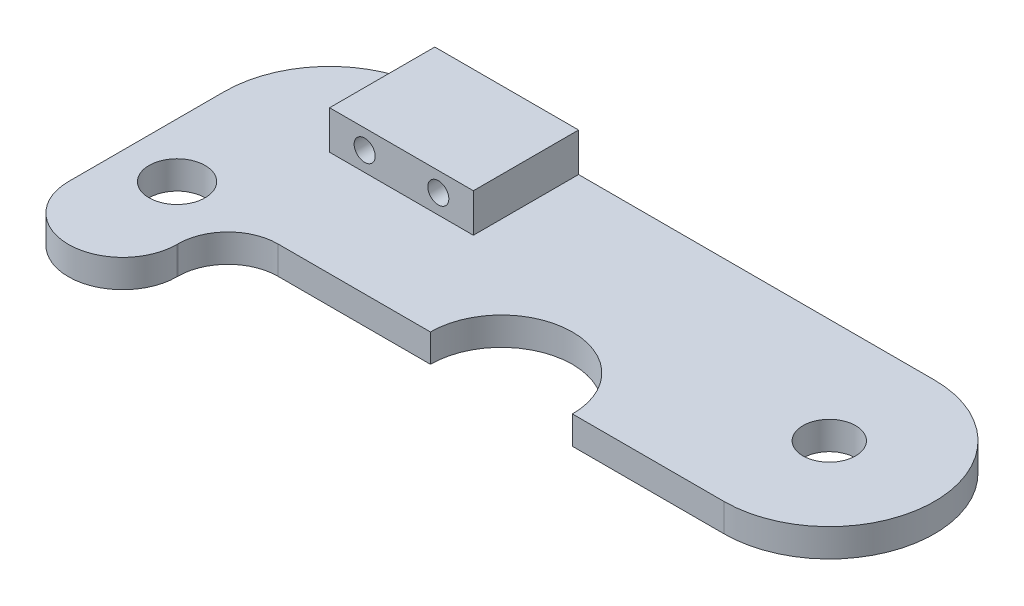
SolidWorks part; units mm, degrees
ref_plane "Front Plane" through (0, 0, 0) normal (0, 0, 1) x (1, 0, 0)
ref_plane "Top Plane" through (0, 0, 0) normal (0, 1, 0) x (1, 0, 0)
ref_plane "Right Plane" through (0, 0, 0) normal (1, 0, 0) x (0, 0, -1)
sketch "Sketch1" plane through (0, 0, 0) normal (0, 1, 0) x (1, 0, 0)
  line L0 (71.9495, -40.7752) -> (158.4495, -40.7752)
  line L1 (-126.5505, 79.2248) -> (158.4495, 79.2248)
  line L3 (-96.0505, -40.7752) -> (-9.0505, -40.7752)
  line L8 (-186.5505, -40.7752) -> (-186.5505, 19.2248)
  line L11 (-186.5505, -40.7752) -> (-186.5505, -69.7752)
  line L13 (-124.5505, -69.2752) -> (-124.5505, -69.7752)
  arc A0 (71.9495, -40.7752) -> (-9.0505, -40.7752) centre (31.4495, -40.7752) ccw
  circle A1 centre (158.4495, 19.2248) radius 15
  arc A2 (158.4495, -40.7752) -> (158.4495, 79.2248) centre (158.4495, 19.2248) ccw
  arc A3 (-126.5505, 79.2248) -> (-186.5505, 19.2248) centre (-126.5505, 19.2248) ccw
  arc A5 (-186.5505, -69.7752) -> (-124.5505, -69.7752) centre (-155.5505, -69.7752) ccw
  circle A6 centre (-155.5505, -38.7752) radius 16
  arc A7 (-96.0505, -40.7752) -> (-124.5505, -69.2752) centre (-96.0505, -69.2752) ccw
  point P14 (0, 0)
  dimension "D3" = 30
  dimension "D4" = 81
  dimension "D8" = 32
  dimension "D1" = 285
  dimension "D2" = 87
  dimension "D6" = 60
  dimension "D7" = 62
  dimension "D9" = 31
extrude "Boss-Extrude2" add sketch "Sketch1" along normal blind 16
scale "Scale1" scale about centroid uniform scaling yes scale factor 0.1
sketch "Sketch2" plane through (0, 8.8, 0) normal (0, 1, 0) x (1, 0, 0)
  line L1 (-12.8704, 21.7021) -> (-4.6704, 21.7021)
  line L2 (-12.8704, 21.7021) -> (-12.8704, 15.7021)
  line L3 (-12.8704, 15.7021) -> (-4.6704, 15.7021)
  line L4 (-4.6704, 21.7021) -> (-4.6704, 15.7021)
  dimension "D1" = 6
  dimension "D2" = 8.2
extrude "Boss-Extrude3" add sketch "Sketch2" along normal blind 2.2
sketch "Sketch3" plane through (0, 0, -21.7021) normal (0, 0, -1) x (-1, 0, 0)
  line L0 (4.6704, 11) -> (12.8704, 11) construction
  line L1 (4.6704, 11) -> (4.6704, 8.8) construction
  line L2 (12.8704, 11) -> (12.8704, 8.8) construction
  circle A0 centre (6.6704, 9.9) radius 0.6
  circle A1 centre (10.8704, 9.9) radius 0.6
  dimension "D1" = 1.2
  dimension "D2" = 1.2
  dimension "D3" = 1.1
  dimension "D4" = 0
  dimension "D5" = 2
  dimension "D6" = 2
extrude "Cut-Extrude1" cut sketch "Sketch3" against normal up to next
